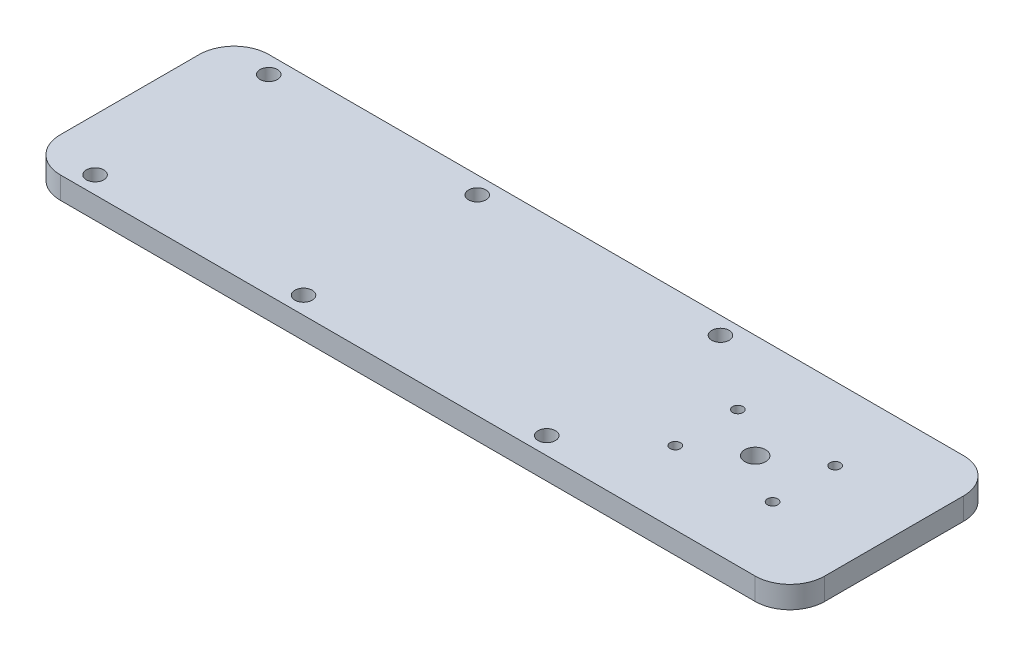
SolidWorks part; units mm, degrees
ref_plane "Front Plane" through (0, 0, 0) normal (0, 0, 1) x (1, 0, 0)
ref_plane "Top Plane" through (0, 0, 0) normal (0, 1, 0) x (1, 0, 0)
ref_plane "Right Plane" through (0, 0, 0) normal (1, 0, 0) x (0, 0, -1)
sketch "Sketch1" plane through (0, 0, 0) normal (0, 1, 0) x (1, 0, 0)
  line L0 (-55, 0) -> (0, 0) construction
  line L1 (-55, 30) -> (165, 30)
  line L2 (-55, 30) -> (-55, -30)
  line L3 (-55, -30) -> (165, -30)
  line L4 (165, 30) -> (165, -30)
  point P7 (125, 0)
  dimension "D1" = 60
  dimension "D2" = 55
  dimension "D3" = 125
  dimension "D4" = 40
extrude "Boss-Extrude1" add sketch "Sketch1" along normal blind 6.35
fillet "Fillet1" radius 10 4 edges at (-55, 3.175, 30) (-55, 3.175, -30) (165, 3.175, 30) (165, 3.175, -30)
hole_wizard "Ø6.0mm Dowel Hole1" positions "Sketch2" profile "Sketch3" hole size "Ø6.0" standard "DIN" end condition up to next
sketch "Sketch2" plane through (0, 6.35, 0) normal (0, 1, 0) x (1, 0, 0)
  point P0 (125, 0)
  dimension "D1" = 125
sketch "Sketch3" plane through (125, 6.35, 0) normal (1, 0, 0) x (0, 0, 1)
  line L0 (0, 0) -> (0, 6.35)
  line L1 (0, 6.35) -> (3, 6.35)
  line L2 (3, 6.35) -> (3, 0)
  line L5 (3, 0) -> (0, 0)
  line L11 (0, -6.35) -> (0, 107.95) construction
  dimension "Thru Hole Dia." = 6
  dimension "Thru Hole Depth" = 6.35
hole_wizard "Ø3.0mm Dowel Hole1" positions "Sketch4" profile "Sketch5" hole size "Ø3.0" standard "ANSI Metric" end condition up to next
sketch "Sketch4" plane through (0, 6.35, 0) normal (0, 1, 0) x (1, 0, 0)
  line L0 (139, -9) -> (111, -9) construction
  line L1 (139, -9) -> (139, 9) construction
  circle A0 centre (125, 0) radius 3 construction
  point P0 (139, -9)
  point P7 (111, -9)
  point P8 (111, 9)
  point P9 (139, 9)
  dimension "D3" = 28
  dimension "D4" = 18
  dimension "D5" = 14
  dimension "D6" = 9
  dimension "D1" = 2
  dimension "D2" = 2
sketch "Sketch5" plane through (139, 6.35, 9) normal (1, 0, 0) x (0, 0, 1)
  line L0 (0, 0) -> (0, 6.35)
  line L1 (0, 6.35) -> (1.5, 6.35)
  line L2 (1.5, 6.35) -> (1.5, 0)
  line L5 (1.5, 0) -> (0, 0)
  line L11 (0, -6.35) -> (0, 107.95) construction
  dimension "Thru Hole Dia." = 3
  dimension "Thru Hole Depth" = 6.35
hole_wizard "Ø5.0mm Dowel Hole1" positions "Sketch6" profile "Sketch7" hole size "Ø5.0" standard "DIN" end condition through all
sketch "Sketch6" plane through (0, 6.35, 0) normal (0, 1, 0) x (1, 0, 0)
  line L0 (-45, -30) -> (155, -30) construction
  line L1 (20, -25) -> (90, -25) construction
  line L2 (-55, 0) -> (165, 0) construction
  line L3 (-55, 20) -> (-55, -20) construction
  line L4 (165, -20) -> (165, 20) construction
  line L5 (55, 30) -> (55, -30) construction
  line L6 (155, 30) -> (-45, 30) construction
  line L8 (20, 25) -> (55, 25) construction
  line L10 (55, 25) -> (90, 25) construction
  point P0 (20, -25)
  point P10 (90, -25)
  point P24 (90, 25)
  point P25 (20, 25)
  point P26 (-40, -25)
  point P29 (-40, 25)
  dimension "D1" = 5
  dimension "D4" = 70
  dimension "D5" = 15
  dimension "D3" = 2
sketch "Sketch7" plane through (20, 6.35, 25) normal (1, 0, 0) x (0, 0, 1)
  line L0 (0, 0) -> (0, 6.35)
  line L1 (0, 6.35) -> (2.5, 6.35)
  line L2 (2.5, 6.35) -> (2.5, 0)
  line L5 (2.5, 0) -> (0, 0)
  line L11 (0, -6.35) -> (0, 107.95) construction
  dimension "Thru Hole Dia." = 5
  dimension "Thru Hole Depth" = 6.35
equation "\"Pivot to Pivot Dist\" = 125mm"
equation "\"D3@Sketch1\"=\"Pivot to Pivot Dist\""
equation "\"D1@Sketch2\"=\"Pivot to Pivot Dist\""
